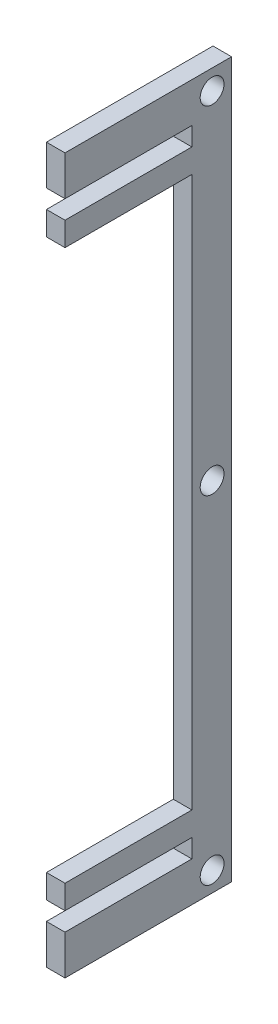
SolidWorks part; units mm, degrees
ref_plane "Front Plane" through (0, 0, 0) normal (1, 0, 0) x (0, 1, 0)
ref_plane "Top Plane" through (0, 0, 0) normal (0, 0, 1) x (0, 1, 0)
ref_plane "Right Plane" through (0, 0, 0) normal (0, 1, 0) x (-1, 0, 0)
sketch "Sketch1" plane through (0, 0, 0) normal (1, 0, 0) x (0, 1, 0)
  line L1 (57.15, -13.3217) -> (-57.15, -13.3217)
  line L2 (57.15, -13.3217) -> (57.15, 13.3217)
  line L3 (57.15, 13.3217) -> (-57.15, 13.3217)
  line L4 (-57.15, -13.3217) -> (-57.15, 13.3217)
  line L5 (57.15, -13.3217) -> (-57.15, 13.3217) construction
  line L6 (57.15, 13.3217) -> (-57.15, -13.3217) construction
  point P0 (0, 0)
  dimension "D1" = 114.3
extrude "Boss-Extrude1" add sketch "Sketch1" along normal blind 2.9718
sketch "Sketch2" plane through (2.9718, 0, 0) normal (1, 0, 0) x (0, 1, 0)
  line L14 (57.15, 13.3217) -> (-57.15, 13.3217) construction
  line L15 (-50.8, 13.3217) -> (-47.8282, 13.3217)
  line L16 (-50.8, 13.3217) -> (-50.8, -6.9717)
  line L17 (-50.8, -6.9717) -> (-47.8282, -6.9717)
  line L18 (-47.8282, 13.3217) -> (-47.8282, -6.9717)
  line L19 (-57.15, -13.3217) -> (57.15, -13.3217) construction
  line L20 (50.8, 13.3217) -> (47.8282, 13.3217)
  line L21 (50.8, 13.3217) -> (50.8, -6.9717)
  line L22 (50.8, -6.9717) -> (47.8282, -6.9717)
  line L23 (47.8282, 13.3217) -> (47.8282, -6.9717)
  line L24 (-44.0182, 13.3217) -> (44.0182, 13.3217)
  line L25 (-44.0182, 13.3217) -> (-44.0182, -6.9717)
  line L26 (-44.0182, -6.9717) -> (44.0182, -6.9717)
  line L27 (44.0182, 13.3217) -> (44.0182, -6.9717)
  line L28 (-57.15, 13.3217) -> (-57.15, -13.3217) construction
  line L29 (57.15, -13.3217) -> (57.15, 13.3217) construction
  point P20 (-49.3141, -6.9717)
  point P21 (49.3141, -6.9717)
  dimension "D1" = 6.35
  dimension "D2" = 6.35
  dimension "D3" = 6.35
  dimension "D4" = 2.9718
  dimension "D5" = 2.9718
  dimension "D6" = 6.35
  dimension "D7" = 6.35
  dimension "D8" = 3.81
  dimension "D9" = 3.81
extrude "Cut-Extrude1" cut sketch "Sketch2" against normal blind 3.175
sketch "Sketch3" plane through (2.9718, 0, 0) normal (1, 0, 0) x (0, 1, 0)
  line L0 (0, 0) -> (0, -20.4185) construction
  line L7 (-67.6823, -10.2093) -> (75.384, -10.2093) construction
  line L8 (-53.975, 13.3217) -> (-53.975, -38.2382) construction
  line L9 (-50.8, 13.3217) -> (-57.15, 13.3217) construction
  line L10 (53.975, 13.3217) -> (53.975, -51.2378) construction
  line L11 (57.15, 13.3217) -> (50.8, 13.3217) construction
  circle A0 centre (0, -10.2093) radius 1.905
  circle A3 centre (-53.975, -10.2093) radius 1.905
  circle A4 centre (53.975, -10.2093) radius 1.905
  dimension "D1" = 3.81
  dimension "D2" = 3.81
  dimension "D3" = 3.81
extrude "Cut-Extrude2" cut sketch "Sketch3" against normal blind 3.175
